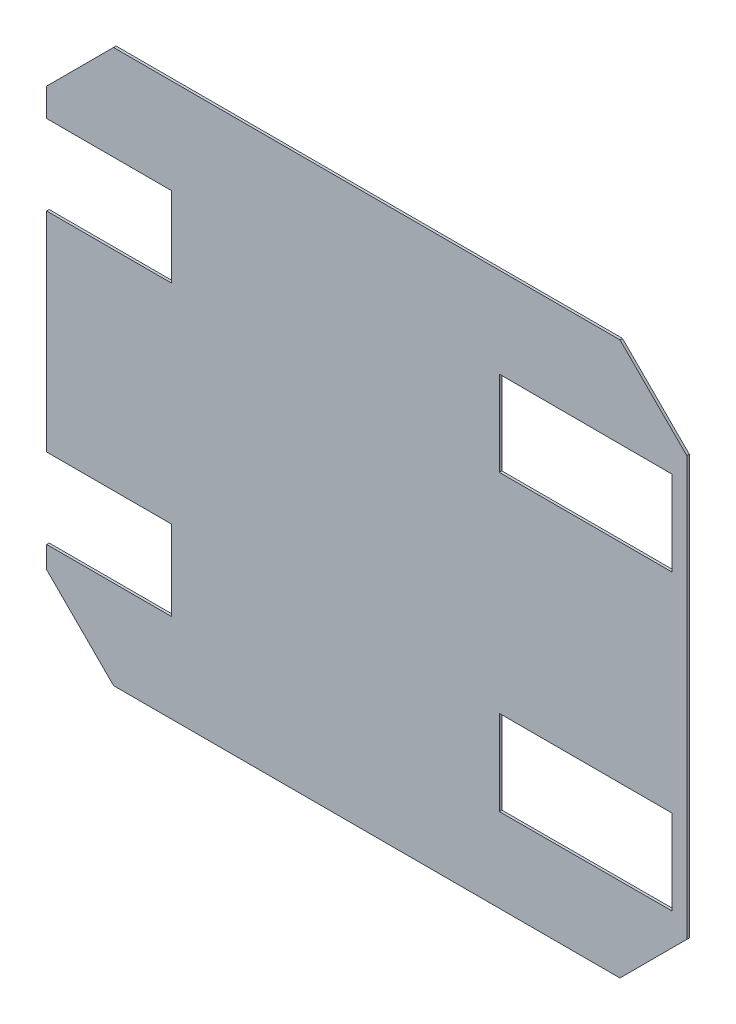
SolidWorks part; units mm, degrees
material "Acier allié inoxydable"
ref_plane "Plan de face" through (0, 0, 0) normal (0, 0, 1) x (1, 0, 0)
ref_plane "Plan de dessus" through (0, 0, 0) normal (0, 1, 0) x (1, 0, 0)
ref_plane "Plan de droite" through (0, 0, 0) normal (1, 0, 0) x (0, 0, -1)
sketch "Esquisse2" plane through (0, 0, 0) normal (0, 0, 1) x (1, 0, 0)
  line L0 (-336.3733, 260.7775) -> (-389.888, 207.2628)
  line L1 (-389.888, 207.2628) -> (-389.888, -127.7078)
  line L2 (-389.888, -127.7078) -> (-336.3733, -181.2225)
  line L3 (-336.3733, -181.2225) -> (68.5973, -181.2225)
  line L4 (68.5973, -181.2225) -> (122.112, -127.7078)
  line L5 (122.112, -127.7078) -> (122.112, 207.2628)
  line L6 (122.112, 207.2628) -> (68.5973, 260.7775)
  line L7 (68.5973, 260.7775) -> (-336.3733, 260.7775)
  line L8 (116.112, 204.7775) -> (66.112, 254.7775)
  line L9 (116.112, -125.2225) -> (116.112, 204.7775)
  line L10 (66.112, -175.2225) -> (116.112, -125.2225)
  line L11 (-333.888, -175.2225) -> (66.112, -175.2225)
  line L12 (-383.888, -125.2225) -> (-333.888, -175.2225)
  line L13 (-383.888, 204.7775) -> (-383.888, -125.2225)
  line L14 (-333.888, 254.7775) -> (-383.888, 204.7775)
  line L15 (66.112, 254.7775) -> (-333.888, 254.7775)
  line L16 (-389.888, 184.7775) -> (-289.888, 184.7775)
  line L17 (-289.888, 184.7775) -> (-289.888, 120.7775)
  line L18 (-289.888, 120.7775) -> (-389.888, 120.7775)
  line L19 (110.112, 188.5477) -> (-27.888, 188.7775)
  line L20 (-27.888, 188.7775) -> (-27.888, 120.7775)
  line L21 (-27.888, 120.7775) -> (110.112, 120.7775)
  line L22 (110.112, 188.5477) -> (110.112, 120.7775)
  line L23 (118.6629, 120.7775) -> (122.112, 120.7775)
  line L24 (-160.3825, 37.3047) -> (-100.9212, 37.3047)
  line L25 (118.6629, -46.1682) -> (122.112, -46.1682)
  line L26 (110.112, -113.9384) -> (110.112, -46.1682)
  line L27 (-27.888, -46.1682) -> (110.112, -46.1682)
  line L28 (-27.888, -114.1682) -> (-27.888, -46.1682)
  line L29 (110.112, -113.9384) -> (-27.888, -114.1682)
  line L30 (-289.888, -46.1682) -> (-389.888, -46.1682)
  line L31 (-289.888, -110.1682) -> (-289.888, -46.1682)
  line L32 (-389.888, -110.1682) -> (-289.888, -110.1682)
  line L34 (-383.888, -125.2225) -> (-383.888, 199.8318)
  line L35 (-389.888, -127.7078) -> (-389.888, 202.3171)
extrude "Boss.-Extru.1" add sketch "Esquisse2" along normal blind 2
sketch "Esquisse4" plane through (0, 0, 0) normal (0, 0, -1) x (-1, 0, 0)
  line L32 (271, -192.4853) -> (271, 192.4853)
  line L33 (271, 192.4853) -> (217.4853, 246)
  line L34 (217.4853, 246) -> (-217.4853, 246)
  line L35 (-217.4853, 246) -> (-271, 192.4853)
  line L36 (-271, 192.4853) -> (-271, 169)
  line L37 (-271, 169) -> (-171, 169)
  line L38 (-171, 169) -> (-171, 81)
  line L39 (-171, 81) -> (-271, 81)
  line L40 (-271, 81) -> (-271, -81)
  line L41 (-271, -81) -> (-171, -81)
  line L42 (-171, -81) -> (-171, -169)
  line L43 (-171, -169) -> (-271, -169)
  line L44 (-271, -169) -> (-271, -192.4853)
  line L45 (-271, -192.4853) -> (-217.4853, -246)
  line L46 (-217.4853, -246) -> (217.4853, -246)
  line L47 (217.4853, -246) -> (271, -192.4853)
  line L49 (-258.8941, 0) -> (259.4772, 0)
  line L50 (-165, 119.7108) -> (-165, 79.0306)
  line L51 (-211.5207, 175) -> (-168.1855, 175)
  line L52 (-242.4915, 212.5085) -> (-262.9882, 192.0118)
  line L53 (-111.0102, 240) -> (-211.4898, 240)
  line L54 (-3.5102, 240) -> (-103.9898, 240)
  line L55 (103.9898, 240) -> (3.5102, 240)
  line L56 (236.5977, 218.4023) -> (218.1776, 236.8224)
  line L57 (265, 99.9161) -> (265, 185.0839)
  line L58 (265, 5.5228) -> (265, 90.0839)
  line L59 (-265, -6.1059) -> (-265, -75)
  line L64 (-165, -75) -> (-165, -175)
  line L65 (-165, -175) -> (-265, -175)
  line L66 (-265, -175) -> (-265, -190)
  line L67 (-265, -190) -> (-215, -240)
  line L68 (-215, -240) -> (215, -240)
  line L69 (215, -240) -> (265, -190)
  line L70 (265, -190) -> (265, -5.5228)
  line L71 (261.5238, 193.4762) -> (243.4023, 211.5977)
  line L72 (210.5062, 240) -> (111.0102, 240)
  line L73 (-217.4821, 237.5179) -> (-237.5085, 217.4915)
  line L74 (-265, 187.1548) -> (-265, 177.7469)
  line L75 (-262.2531, 175) -> (-218.4793, 175)
  line L76 (-165, 171.8145) -> (-165, 130.2892)
  line L77 (-169.0306, 75) -> (-261.5627, 75)
  line L78 (-265, 71.5627) -> (-265, 6.1059)
  line L79 (-265, -75) -> (-165, -75)
  circle A2 centre (-265, 75) radius 3.4373
  circle A4 centre (-165, 75) radius 4.0306
  circle A6 centre (265, 0) radius 5.5228
  circle A8 centre (240, 215) radius 4.8115
  circle A10 centre (265, 190) radius 4.9161
  circle A12 centre (215, 240) radius 4.4938
  circle A14 centre (-215, 240) radius 3.5102
  circle A16 centre (-240, 215) radius 3.5235
  circle A18 centre (-215, 175) radius 3.4793
  circle A20 centre (-265, 190) radius 2.8452
  circle A22 centre (-265, 175) radius 2.7469
  circle A24 centre (-165, 175) radius 3.1855
  circle A26 centre (-265, 0) radius 6.1059
  circle A28 centre (265, 95) radius 4.9161
  circle A32 centre (107.5, 240) radius 3.5102
  circle A34 centre (0, 240) radius 3.5102
  circle A36 centre (-107.5, 240) radius 3.5102
  circle A38 centre (-165, 125) radius 5.2892
ref_plane "Plan1" through (0, 37.3047, 0) normal (0, 1, 0) x (1, 0, 0)
